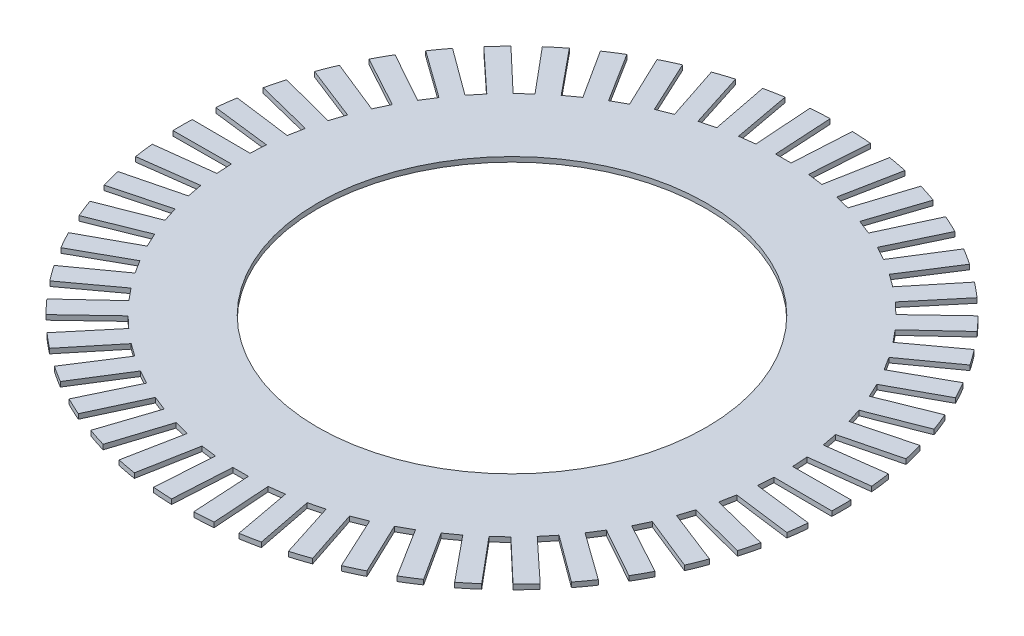
SolidWorks part; units mm, degrees
ref_plane "Front Plane" through (0, 0, 0) normal (0, 0, 1) x (1, 0, 0)
ref_plane "Top Plane" through (0, 0, 0) normal (0, 1, 0) x (1, 0, 0)
ref_plane "Right Plane" through (0, 0, 0) normal (1, 0, 0) x (0, 0, -1)
sketch "Sketch1" plane through (0, 0, 0) normal (0, 1, 0) x (1, 0, 0)
  circle A0 centre (0, 0) radius 20.05
  circle A1 centre (0, 0) radius 34
extrude "Boss-Extrude2" add sketch "Sketch1" along normal blind 0.5
sketch "Sketch2" plane through (0, 0.5, 0) normal (0, 1, 0) x (1, 0, 0)
  line L0 (0, 0) -> (0, 32.1339) construction
  line L1 (-1.2, 34.9172) -> (1.2, 34.9172)
  line L2 (1.2, 34.9172) -> (0.8, 28.0001)
  line L3 (0.8, 28.0001) -> (-0.8, 28.0001)
  line L4 (0, 34.0001) -> (10.071, 34.0001) construction
  line L5 (-1.2, 34.9172) -> (-0.8, 28.0001)
  line L6 (3.1858, 34.7923) -> (5.5668, 34.4915)
  line L7 (5.5668, 34.4915) -> (4.303, 27.679)
  line L8 (4.303, 27.679) -> (2.7156, 27.8795)
  line L9 (3.1858, 34.7923) -> (2.7156, 27.8795)
  line L10 (7.5213, 34.1187) -> (9.8459, 33.5218)
  line L11 (9.8459, 33.5218) -> (7.7382, 26.9214)
  line L12 (7.7382, 26.9214) -> (6.1885, 27.3193)
  line L13 (7.5213, 34.1187) -> (6.1885, 27.3193)
  line L14 (11.7382, 32.907) -> (13.9696, 32.0235)
  line L15 (13.9696, 32.0235) -> (11.0513, 25.7393)
  line L16 (11.0513, 25.7393) -> (9.5637, 26.3283)
  line L17 (11.7382, 32.907) -> (9.5637, 26.3283)
  line L18 (15.7699, 31.1763) -> (17.8731, 30.0201)
  line L19 (17.8731, 30.0201) -> (14.1902, 24.1512)
  line L20 (14.1902, 24.1512) -> (12.7881, 24.922)
  line L21 (15.7699, 31.1763) -> (12.7881, 24.922)
  line L22 (19.553, 28.954) -> (21.4947, 27.5433)
  line L23 (21.4947, 27.5433) -> (17.1052, 22.1823)
  line L24 (17.1052, 22.1823) -> (15.8108, 23.1228)
  line L25 (19.553, 28.954) -> (15.8108, 23.1228)
  line L26 (23.0277, 26.275) -> (24.7773, 24.6321)
  line L27 (24.7773, 24.6321) -> (19.7505, 19.8635)
  line L28 (19.7505, 19.8635) -> (18.5842, 20.9588)
  line L29 (23.0277, 26.275) -> (18.5842, 20.9588)
  line L30 (26.1393, 23.1817) -> (27.6691, 21.3325)
  line L31 (27.6691, 21.3325) -> (22.0844, 17.2315)
  line L32 (22.0844, 17.2315) -> (21.0645, 18.4643)
  line L33 (26.1393, 23.1817) -> (21.0645, 18.4643)
  line L34 (28.8386, 19.7228) -> (30.1246, 17.6964)
  line L35 (30.1246, 17.6964) -> (24.0699, 14.3277)
  line L36 (24.0699, 14.3277) -> (23.2126, 15.6786)
  line L37 (28.8386, 19.7228) -> (23.2126, 15.6786)
  line L38 (31.0831, 15.9528) -> (32.105, 13.7812)
  line L39 (32.105, 13.7812) -> (25.6758, 11.198)
  line L40 (25.6758, 11.198) -> (24.9946, 12.6457)
  line L41 (31.0831, 15.9528) -> (24.9946, 12.6457)
  line L42 (32.8375, 11.9313) -> (33.5791, 9.6488)
  line L43 (33.5791, 9.6488) -> (26.8769, 7.8916)
  line L44 (26.8769, 7.8916) -> (26.3824, 9.4133)
  line L45 (32.8375, 11.9313) -> (26.3824, 9.4133)
  line L46 (34.0739, 7.7216) -> (34.5236, 5.3641)
  line L47 (34.5236, 5.3641) -> (27.654, 4.4609)
  line L48 (27.654, 4.4609) -> (27.3542, 6.0325)
  line L49 (34.0739, 7.7216) -> (27.3542, 6.0325)
  line L50 (34.773, 3.3901) -> (34.9237, 0.9948)
  line L51 (34.9237, 0.9948) -> (27.995, 0.9597)
  line L52 (27.995, 0.9597) -> (27.8946, 2.5566)
  line L53 (34.773, 3.3901) -> (27.8946, 2.5566)
  line L54 (34.9237, -0.9948) -> (34.773, -3.3901)
  line L55 (34.773, -3.3901) -> (27.8946, -2.5566)
  line L56 (27.8946, -2.5566) -> (27.995, -0.9597)
  line L57 (34.9237, -0.9948) -> (27.995, -0.9597)
  line L58 (34.5236, -5.3641) -> (34.0739, -7.7216)
  line L59 (34.0739, -7.7216) -> (27.3542, -6.0325)
  line L60 (27.3542, -6.0325) -> (27.654, -4.4609)
  line L61 (34.5236, -5.3641) -> (27.654, -4.4609)
  line L62 (33.5791, -9.6488) -> (32.8375, -11.9313)
  line L63 (32.8375, -11.9313) -> (26.3824, -9.4133)
  line L64 (26.3824, -9.4133) -> (26.8769, -7.8916)
  line L65 (33.5791, -9.6488) -> (26.8769, -7.8916)
  line L66 (32.105, -13.7812) -> (31.0831, -15.9528)
  line L67 (31.0831, -15.9528) -> (24.9946, -12.6457)
  line L68 (24.9946, -12.6457) -> (25.6758, -11.198)
  line L69 (32.105, -13.7812) -> (25.6758, -11.198)
  line L70 (30.1246, -17.6964) -> (28.8386, -19.7228)
  line L71 (28.8386, -19.7228) -> (23.2126, -15.6786)
  line L72 (23.2126, -15.6786) -> (24.0699, -14.3277)
  line L73 (30.1246, -17.6964) -> (24.0699, -14.3277)
  line L74 (27.6691, -21.3325) -> (26.1393, -23.1817)
  line L75 (26.1393, -23.1817) -> (21.0645, -18.4643)
  line L76 (21.0645, -18.4643) -> (22.0844, -17.2315)
  line L77 (27.6691, -21.3325) -> (22.0844, -17.2315)
  line L78 (24.7773, -24.6321) -> (23.0277, -26.275)
  line L79 (23.0277, -26.275) -> (18.5842, -20.9588)
  line L80 (18.5842, -20.9588) -> (19.7505, -19.8635)
  line L81 (24.7773, -24.6321) -> (19.7505, -19.8635)
  line L82 (21.4947, -27.5433) -> (19.553, -28.954)
  line L83 (19.553, -28.954) -> (15.8108, -23.1228)
  line L84 (15.8108, -23.1228) -> (17.1052, -22.1823)
  line L85 (21.4947, -27.5433) -> (17.1052, -22.1823)
  line L86 (17.8731, -30.0201) -> (15.7699, -31.1763)
  line L87 (15.7699, -31.1763) -> (12.7881, -24.922)
  line L88 (12.7881, -24.922) -> (14.1902, -24.1512)
  line L89 (17.8731, -30.0201) -> (14.1902, -24.1512)
  line L90 (13.9696, -32.0235) -> (11.7382, -32.907)
  line L91 (11.7382, -32.907) -> (9.5637, -26.3283)
  line L92 (9.5637, -26.3283) -> (11.0513, -25.7393)
  line L93 (13.9696, -32.0235) -> (11.0513, -25.7393)
  line L94 (9.8459, -33.5218) -> (7.5213, -34.1187)
  line L95 (7.5213, -34.1187) -> (6.1885, -27.3193)
  line L96 (6.1885, -27.3193) -> (7.7382, -26.9214)
  line L97 (9.8459, -33.5218) -> (7.7382, -26.9214)
  line L98 (5.5668, -34.4915) -> (3.1858, -34.7923)
  line L99 (3.1858, -34.7923) -> (2.7156, -27.8795)
  line L100 (2.7156, -27.8795) -> (4.303, -27.679)
  line L101 (5.5668, -34.4915) -> (4.303, -27.679)
  line L102 (1.2, -34.9172) -> (-1.2, -34.9172)
  line L103 (-1.2, -34.9172) -> (-0.8, -28.0001)
  line L104 (-0.8, -28.0001) -> (0.8, -28.0001)
  line L105 (1.2, -34.9172) -> (0.8, -28.0001)
  line L106 (-3.1858, -34.7923) -> (-5.5668, -34.4915)
  line L107 (-5.5668, -34.4915) -> (-4.303, -27.679)
  line L108 (-4.303, -27.679) -> (-2.7156, -27.8795)
  line L109 (-3.1858, -34.7923) -> (-2.7156, -27.8795)
  line L110 (-7.5213, -34.1187) -> (-9.8459, -33.5218)
  line L111 (-9.8459, -33.5218) -> (-7.7382, -26.9214)
  line L112 (-7.7382, -26.9214) -> (-6.1885, -27.3193)
  line L113 (-7.5213, -34.1187) -> (-6.1885, -27.3193)
  line L114 (-11.7382, -32.907) -> (-13.9696, -32.0235)
  line L115 (-13.9696, -32.0235) -> (-11.0513, -25.7393)
  line L116 (-11.0513, -25.7393) -> (-9.5637, -26.3283)
  line L117 (-11.7382, -32.907) -> (-9.5637, -26.3283)
  line L118 (-15.7699, -31.1763) -> (-17.8731, -30.0201)
  line L119 (-17.8731, -30.0201) -> (-14.1902, -24.1512)
  line L120 (-14.1902, -24.1512) -> (-12.7881, -24.922)
  line L121 (-15.7699, -31.1763) -> (-12.7881, -24.922)
  line L122 (-19.553, -28.954) -> (-21.4947, -27.5433)
  line L123 (-21.4947, -27.5433) -> (-17.1052, -22.1823)
  line L124 (-17.1052, -22.1823) -> (-15.8108, -23.1228)
  line L125 (-19.553, -28.954) -> (-15.8108, -23.1228)
  line L126 (-23.0277, -26.275) -> (-24.7773, -24.6321)
  line L127 (-24.7773, -24.6321) -> (-19.7505, -19.8635)
  line L128 (-19.7505, -19.8635) -> (-18.5842, -20.9588)
  line L129 (-23.0277, -26.275) -> (-18.5842, -20.9588)
  line L130 (-26.1393, -23.1817) -> (-27.6691, -21.3325)
  line L131 (-27.6691, -21.3325) -> (-22.0844, -17.2315)
  line L132 (-22.0844, -17.2315) -> (-21.0645, -18.4643)
  line L133 (-26.1393, -23.1817) -> (-21.0645, -18.4643)
  line L134 (-28.8386, -19.7228) -> (-30.1246, -17.6964)
  line L135 (-30.1246, -17.6964) -> (-24.0699, -14.3277)
  line L136 (-24.0699, -14.3277) -> (-23.2126, -15.6786)
  line L137 (-28.8386, -19.7228) -> (-23.2126, -15.6786)
  line L138 (-31.0831, -15.9528) -> (-32.105, -13.7812)
  line L139 (-32.105, -13.7812) -> (-25.6758, -11.198)
  line L140 (-25.6758, -11.198) -> (-24.9946, -12.6457)
  line L141 (-31.0831, -15.9528) -> (-24.9946, -12.6457)
  line L142 (-32.8375, -11.9313) -> (-33.5791, -9.6488)
  line L143 (-33.5791, -9.6488) -> (-26.8769, -7.8916)
  line L144 (-26.8769, -7.8916) -> (-26.3824, -9.4133)
  line L145 (-32.8375, -11.9313) -> (-26.3824, -9.4133)
  line L146 (-34.0739, -7.7216) -> (-34.5236, -5.3641)
  line L147 (-34.5236, -5.3641) -> (-27.654, -4.4609)
  line L148 (-27.654, -4.4609) -> (-27.3542, -6.0325)
  line L149 (-34.0739, -7.7216) -> (-27.3542, -6.0325)
  line L150 (-34.773, -3.3901) -> (-34.9237, -0.9948)
  line L151 (-34.9237, -0.9948) -> (-27.995, -0.9597)
  line L152 (-27.995, -0.9597) -> (-27.8946, -2.5566)
  line L153 (-34.773, -3.3901) -> (-27.8946, -2.5566)
  line L154 (-34.9237, 0.9948) -> (-34.773, 3.3901)
  line L155 (-34.773, 3.3901) -> (-27.8946, 2.5566)
  line L156 (-27.8946, 2.5566) -> (-27.995, 0.9597)
  line L157 (-34.9237, 0.9948) -> (-27.995, 0.9597)
  line L158 (-34.5236, 5.3641) -> (-34.0739, 7.7216)
  line L159 (-34.0739, 7.7216) -> (-27.3542, 6.0325)
  line L160 (-27.3542, 6.0325) -> (-27.654, 4.4609)
  line L161 (-34.5236, 5.3641) -> (-27.654, 4.4609)
  line L162 (-33.5791, 9.6488) -> (-32.8375, 11.9313)
  line L163 (-32.8375, 11.9313) -> (-26.3824, 9.4133)
  line L164 (-26.3824, 9.4133) -> (-26.8769, 7.8916)
  line L165 (-33.5791, 9.6488) -> (-26.8769, 7.8916)
  line L166 (-32.105, 13.7812) -> (-31.0831, 15.9528)
  line L167 (-31.0831, 15.9528) -> (-24.9946, 12.6457)
  line L168 (-24.9946, 12.6457) -> (-25.6758, 11.198)
  line L169 (-32.105, 13.7812) -> (-25.6758, 11.198)
  line L170 (-30.1246, 17.6964) -> (-28.8386, 19.7228)
  line L171 (-28.8386, 19.7228) -> (-23.2126, 15.6786)
  line L172 (-23.2126, 15.6786) -> (-24.0699, 14.3277)
  line L173 (-30.1246, 17.6964) -> (-24.0699, 14.3277)
  line L174 (-27.6691, 21.3325) -> (-26.1393, 23.1817)
  line L175 (-26.1393, 23.1817) -> (-21.0645, 18.4643)
  line L176 (-21.0645, 18.4643) -> (-22.0844, 17.2315)
  line L177 (-27.6691, 21.3325) -> (-22.0844, 17.2315)
  line L178 (-24.7773, 24.6321) -> (-23.0277, 26.275)
  line L179 (-23.0277, 26.275) -> (-18.5842, 20.9588)
  line L180 (-18.5842, 20.9588) -> (-19.7505, 19.8635)
  line L181 (-24.7773, 24.6321) -> (-19.7505, 19.8635)
  line L182 (-21.4947, 27.5433) -> (-19.553, 28.954)
  line L183 (-19.553, 28.954) -> (-15.8108, 23.1228)
  line L184 (-15.8108, 23.1228) -> (-17.1052, 22.1823)
  line L185 (-21.4947, 27.5433) -> (-17.1052, 22.1823)
  line L186 (-17.8731, 30.0201) -> (-15.7699, 31.1763)
  line L187 (-15.7699, 31.1763) -> (-12.7881, 24.922)
  line L188 (-12.7881, 24.922) -> (-14.1902, 24.1512)
  line L189 (-17.8731, 30.0201) -> (-14.1902, 24.1512)
  line L190 (-13.9696, 32.0235) -> (-11.7382, 32.907)
  line L191 (-11.7382, 32.907) -> (-9.5637, 26.3283)
  line L192 (-9.5637, 26.3283) -> (-11.0513, 25.7393)
  line L193 (-13.9696, 32.0235) -> (-11.0513, 25.7393)
  line L194 (-9.8459, 33.5218) -> (-7.5213, 34.1187)
  line L195 (-7.5213, 34.1187) -> (-6.1885, 27.3193)
  line L196 (-6.1885, 27.3193) -> (-7.7382, 26.9214)
  line L197 (-9.8459, 33.5218) -> (-7.7382, 26.9214)
  line L198 (-5.5668, 34.4915) -> (-3.1858, 34.7923)
  line L199 (-3.1858, 34.7923) -> (-2.7156, 27.8795)
  line L200 (-2.7156, 27.8795) -> (-4.303, 27.679)
  line L201 (-5.5668, 34.4915) -> (-4.303, 27.679)
  point P207 (0, 0)
  dimension "D1" = 6
  dimension "D2" = 2.4
  dimension "D3" = 1.6
  dimension "D4" = 50
extrude "Cut-Extrude1" cut sketch "Sketch2" against normal blind 0.5
